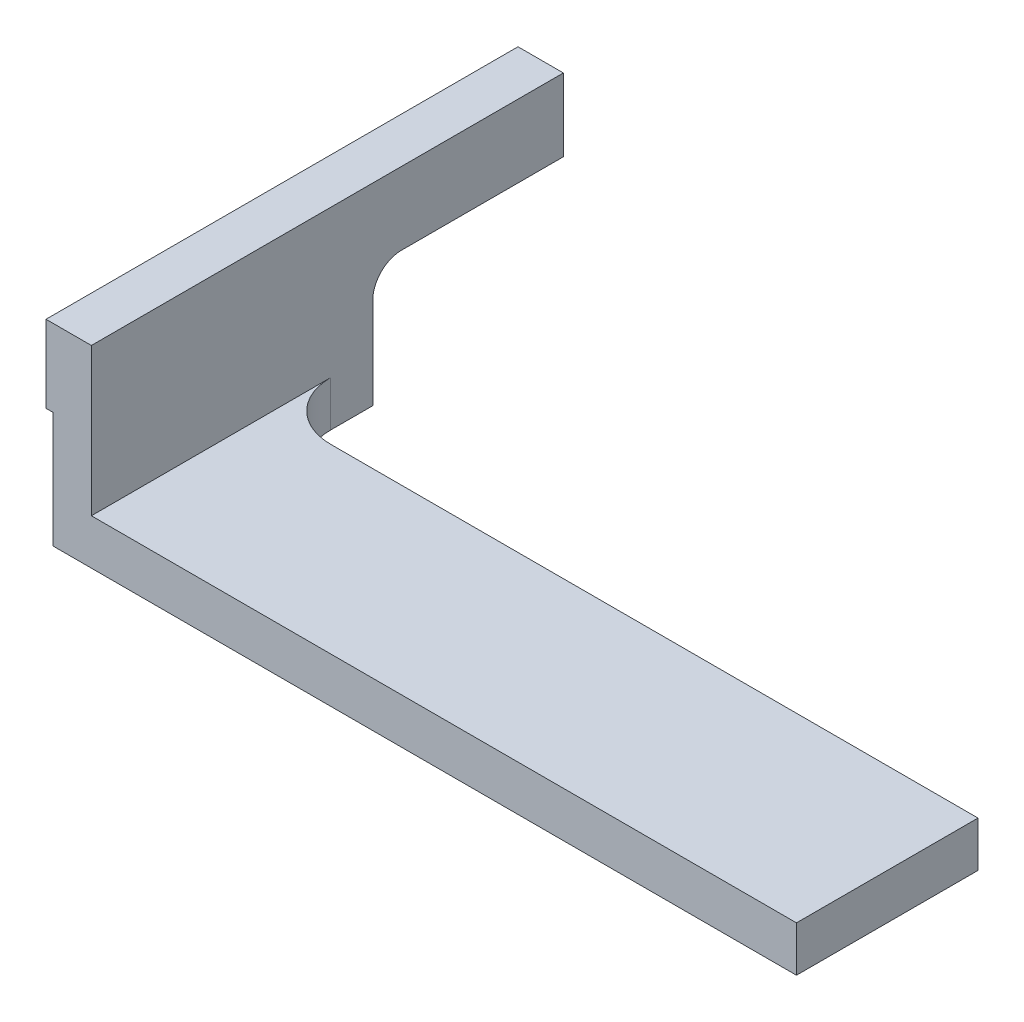
SolidWorks part; units mm, degrees
material "Aluminum Black Anodize"
ref_plane "Front" through (0, 0, 0) normal (0, 0, 1) x (1, 0, 0)
ref_plane "Top" through (0, 0, 0) normal (0, 1, 0) x (1, 0, 0)
ref_plane "Right" through (0, 0, 0) normal (1, 0, 0) x (0, 0, -1)
sketch "Sketch1" plane through (0, 0, 0) normal (0, 0, 1) x (1, 0, 0)
  line L0 (0, 0) -> (0, 21.25)
  line L1 (0, 21.25) -> (5, 21.25)
  line L2 (5, 21.25) -> (5, 5)
  line L3 (5, 5) -> (82.68, 5)
  line L4 (82.68, 5) -> (82.68, 0)
  line L5 (82.68, 0) -> (0, 0)
  dimension "D1" = 82.68
  dimension "D2" = 21.25
  dimension "D3" = 5
extrude "Extrude1" add sketch "Sketch1" along normal mid plane 52
sketch "Sketch24" plane through (0, 5, 0) normal (0, 1, 0) x (1, 0, 0)
  line L0 (5, -26) -> (5, 26) construction
  line L1 (82.68, -6) -> (5, -6)
  line L2 (82.68, -6) -> (82.68, 26)
  line L3 (82.68, 26) -> (5, 26)
  line L4 (5, -6) -> (5, 26)
  line L6 (82.68, -26) -> (82.68, 26) construction
  line L7 (82.68, -26) -> (5, -26) construction
  dimension "D1" = 20
extrude "Cut-Extrude1" cut sketch "Sketch24" against normal through all
fillet "Fillet1" radius 6.35 1 edges at (5, 2.5, 6)
sketch "Sketch25" plane through (0, 0, 26) normal (0, 0, 1) x (1, 0, 0)
  line L0 (5, 21.25) -> (0, 21.25) construction
  line L1 (0, 0) -> (0.75, 0)
  line L2 (0, 0) -> (0, 12.75)
  line L3 (0, 12.75) -> (0.75, 12.75)
  line L4 (0.75, 0) -> (0.75, 12.75)
  dimension "D1" = 8.5
  dimension "D2" = 0.75
extrude "Cut-Extrude2" cut sketch "Sketch25" against normal through all
sketch "Sketch30" plane through (5, 0, 0) normal (1, 0, 0) x (0, 0, -1)
  line L1 (26, 0) -> (5, 0)
  line L2 (26, 0) -> (26, 13.25)
  line L3 (26, 13.25) -> (8.175, 13.25)
  line L4 (5, 0) -> (5, 10.075)
  arc A0 (8.175, 13.25) -> (5, 10.075) centre (8.175, 10.075) ccw
  dimension "D3" = 3.175
  dimension "D1" = 21
  dimension "D2" = 13.25
extrude "Cut-Extrude5" cut sketch "Sketch30" against normal through all
sketch "Sketch31" plane through (5, 0, 0) normal (1, 0, 0) x (0, 0, -1)
  line L0 (26, 13.25) -> (26, 21.25) construction
  line L1 (-26, 21.25) -> (26, 21.25) construction
  circle A0 centre (5.5, 17.25) radius 2.286
  circle A1 centre (20.5, 17.25) radius 2.286
  dimension "D1" = 15
  dimension "D2" = 5.5
  dimension "D3" = 4.572
  dimension "D4" = 4
